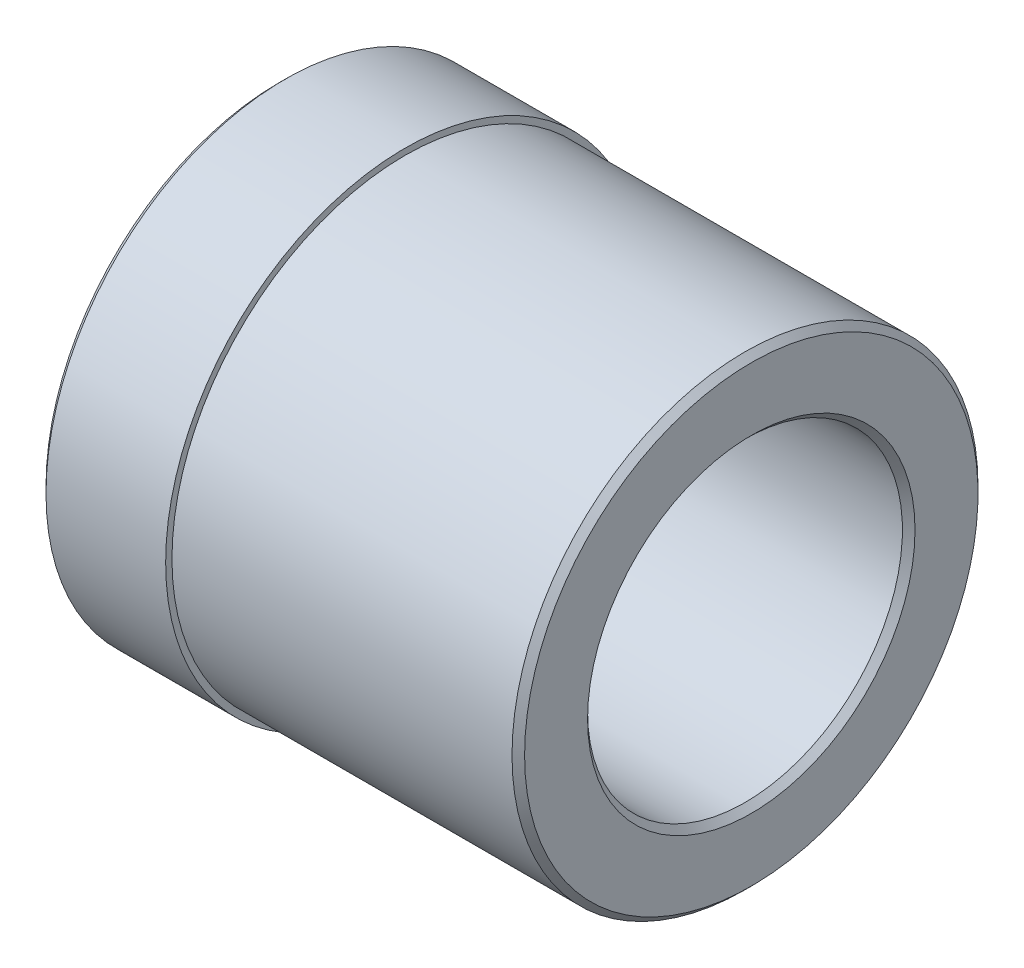
SolidWorks part; units mm, degrees
material "20"
ref_plane "前视基准面" through (0, 0, 0) normal (0, 0, 1) x (1, 0, 0)
ref_plane "上视基准面" through (0, 0, 0) normal (0, 1, 0) x (1, 0, 0)
ref_plane "右视基准面" through (0, 0, 0) normal (1, 0, 0) x (0, 0, -1)
sketch "草图1" plane through (0, 0, 0) normal (0, 0, 1) x (1, 0, 0)
  line L0 (0, 0) -> (79.0846, 0) construction
  line L1 (0, 25) -> (0, 38)
  line L2 (0, 38) -> (20, 38)
  line L3 (20, 38) -> (20, 37)
  line L4 (20, 37) -> (75, 37)
  line L5 (75, 37) -> (75, 25)
  line L6 (0, 25) -> (75, 25)
  line L7 (0, 25) -> (0, 0) construction
  dimension "D1" = 76
  dimension "D2" = 20
  dimension "D3" = 50
  dimension "D4" = 74
  dimension "D5" = 75
revolve "旋转1" add sketch "草图1" angle 360 about L0
chamfer "倒角1" distance 1 angle 45 4 edges at (0, 0, 25) (0, 0, 38) (75, 0, 25) (75, 0, 37)
